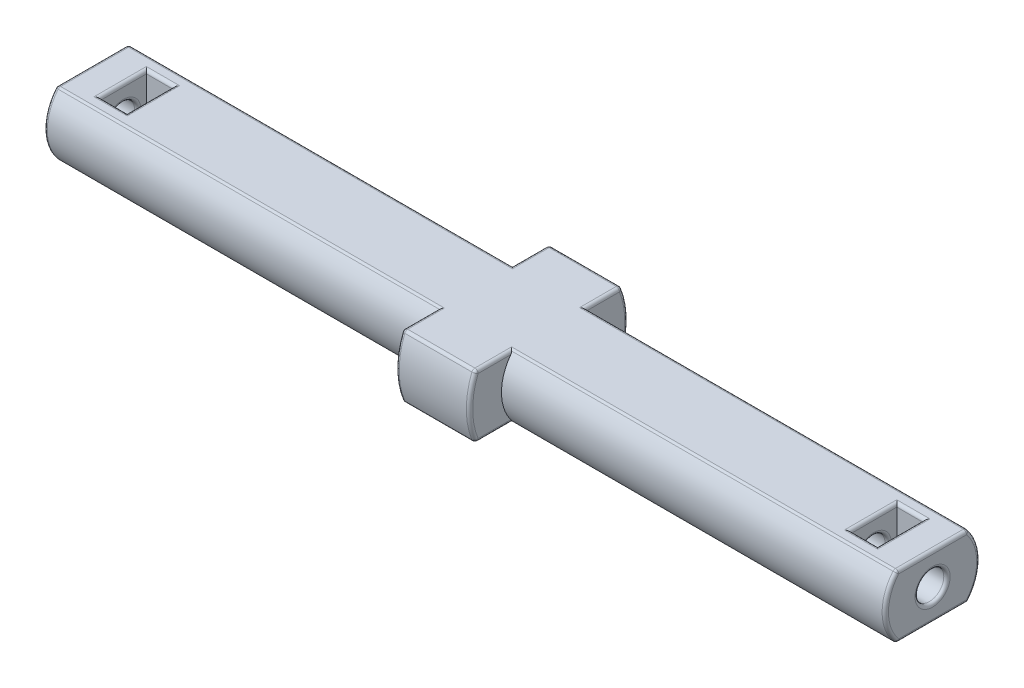
SolidWorks part; units mm, degrees
ref_plane "Front Plane" through (0, 0, 0) normal (0, 0, 1) x (1, 0, 0)
ref_plane "Top Plane" through (0, 0, 0) normal (0, 1, 0) x (1, 0, 0)
ref_plane "Right Plane" through (0, 0, 0) normal (1, 0, 0) x (0, 0, -1)
sketch "Sketch1" plane through (0, 0, 0) normal (0, 1, 0) x (1, 0, 0)
  line L0 (-104.5444, 0) -> (40.6441, 0) construction
  line L1 (-65.8, 0) -> (-65.8, 7.4)
  line L2 (-65.8, 7.4) -> (-5.75, 7.4)
  line L3 (-5.75, 7.4) -> (-5.75, 12.4)
  line L4 (-5.75, 12.4) -> (5.75, 12.4)
  line L5 (5.75, 12.4) -> (5.75, 7.4)
  line L6 (5.75, 7.4) -> (65.8, 7.4)
  line L7 (65.8, 7.4) -> (65.8, 0)
  line L8 (65.8, 0) -> (-65.8, 0)
  dimension "D1" = 131.6
  dimension "D2" = 7.4
  dimension "D3" = 12.4
  dimension "D4" = 11.5
revolve "Revolve1" add sketch "Sketch1" angle 360 about L0
sketch "Sketch2" plane through (0, 0, 0) normal (0, 0, 1) x (1, 0, 0)
  line L0 (-65.8, 7.4) -> (-65.8, -7.4) construction
  line L1 (65.8, 4.9) -> (-65.8, 4.9)
  line L2 (65.8, 4.9) -> (65.8, -4.9)
  line L3 (65.8, -4.9) -> (-65.8, -4.9)
  line L4 (-65.8, 4.9) -> (-65.8, -4.9)
  line L5 (65.8, 4.9) -> (-65.8, -4.9) construction
  line L6 (65.8, -4.9) -> (-65.8, 4.9) construction
  line L8 (65.8, -20) -> (-65.8, -20)
  line L9 (65.8, -20) -> (65.8, 20)
  line L10 (65.8, 20) -> (-65.8, 20)
  line L11 (-65.8, -20) -> (-65.8, 20)
  line L12 (65.8, -20) -> (-65.8, 20) construction
  line L13 (65.8, 20) -> (-65.8, -20) construction
  point P0 (0, 0)
  point P6 (0, 0)
  dimension "D1" = 9.8
  dimension "D2" = 40
extrude "Cut-Extrude1" cut sketch "Sketch2" against normal through all both and the other way through all contours L11 L1 L9 L10 | L11 L8 L9 L3
sketch "Sketch3" plane through (65.8, 0, 0) normal (1, 0, 0) x (0, 0, -1)
  circle A0 centre (0, 0) radius 2.25
  dimension "D1" = 4.5
sketch "Sketch4" plane through (-65.8, 0, 0) normal (-1, 0, 0) x (0, 0, 1)
  circle A0 centre (0, 0) radius 2.25
  dimension "D1" = 4.5
extrude "Cut-Extrude2" cut sketch "Sketch3" against normal blind 15
extrude "Cut-Extrude3" cut sketch "Sketch4" against normal blind 15
ref_plane "Plane1" through (-60.8, 0, 0) normal (-1, 0, 0) x (0, 0, 1)
sketch "Sketch5" plane through (-60.8, 0, 0) normal (-1, 0, 0) x (0, 0, 1)
  line L0 (0, 0) -> (0, 4.1569) construction
  line L1 (0, -4.1569) -> (3.6, -2.0785)
  line L2 (3.6, -2.0785) -> (3.6, 2.0785)
  line L3 (3.6, 2.0785) -> (0, 4.1569)
  line L4 (0, 4.1569) -> (-3.6, 2.0785)
  line L5 (-3.6, 2.0785) -> (-3.6, -2.0785)
  line L6 (-3.6, -2.0785) -> (0, -4.1569)
  line L7 (-3.6, 2.0785) -> (-3.6, 4.9)
  line L8 (-5.5453, 4.9) -> (5.5453, 4.9) construction
  line L9 (-3.6, 4.9) -> (3.6, 4.9)
  line L10 (3.6, 4.9) -> (3.6, 2.0785)
  circle A0 centre (0, 0) radius 3.6 construction
  dimension "D1" = 7.2
extrude "Cut-Extrude4" cut sketch "Sketch5" against normal blind 4.2 contours L10 L9 L7 L4 L3 | L5 L6 L1 L2 L3 L4
mirror "Mirror1" about plane through (0, 0, 0) normal (1, 0, 0) of "Cut-Extrude4"
fillet "Fillet1" radius 0.5 45 edges at (60.8, 4.9, 0) (60.8, 0, -2.25) (58.7, 4.9, -3.6) (56.6, 4.9, 0) (58.7, 4.9, 3.6) (56.6, 0, -2.25) (-5.75, 0, -12.4) (-5.75, 0, 12.4) (-5.75, -4.9, 8.468) (-5.75, -4.9, -8.468) (-5.75, 4.9, 8.468) (-5.75, 4.9, -8.468) (5.75, 0, -12.4) (5.75, 0, 12.4) (65.8, 0, -7.4) (65.8, 0, 7.4) (-65.8, 0, -7.4) (-65.8, 0, 7.4) (-65.8, 4.9, 0) (65.8, 4.9, 0) (-35.775, 4.9, -5.5453) (35.775, 4.9, -5.5453) (5.75, 4.9, -8.468) (0, 4.9, -11.3908) (-35.775, 4.9, 5.5453) (0, 4.9, 11.3908) (5.75, 4.9, 8.468) (35.775, 4.9, 5.5453) (65.8, -4.9, 0) (-35.775, -4.9, -5.5453) (-65.8, -4.9, 0) (-35.775, -4.9, 5.5453) (0, -4.9, 11.3908) (5.75, -4.9, 8.468) (35.775, -4.9, 5.5453) (35.775, -4.9, -5.5453) (5.75, -4.9, -8.468) (0, -4.9, -11.3908) (65.8, 0, -2.25) (-56.6, 4.9, 0) (-60.8, 0, 2.25) (-60.8, 4.9, 0) (-58.7, 4.9, -3.6) (-58.7, 4.9, 3.6) (-56.6, 0, 2.25)
